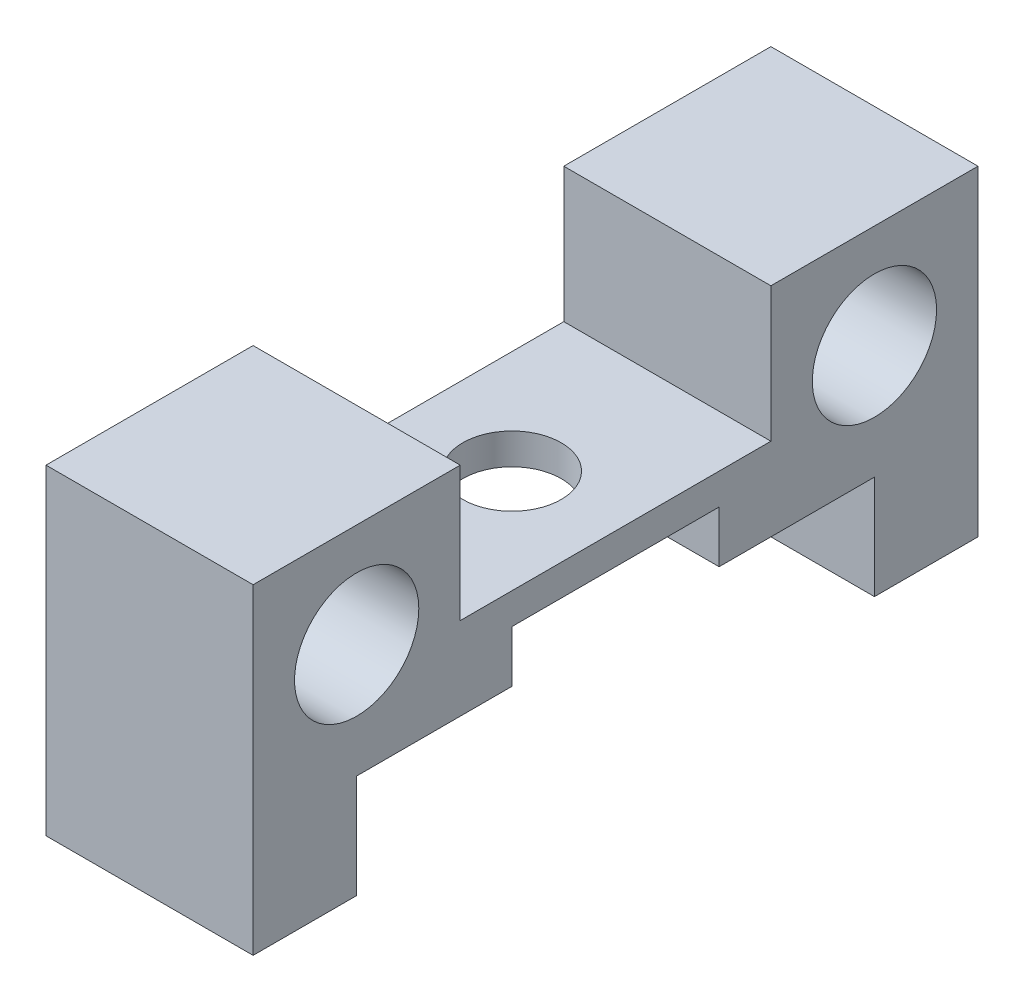
SolidWorks part; units mm, degrees
ref_plane "Plan de face" through (0, 0, 0) normal (0, 0, 1) x (1, 0, 0)
ref_plane "Plan de dessus" through (0, 0, 0) normal (0, 1, 0) x (1, 0, 0)
ref_plane "Plan de droite" through (0, 0, 0) normal (1, 0, 0) x (0, 0, -1)
sketch "Esquisse1" plane through (0, 0, 0) normal (0, 0, 1) x (1, 0, 0)
  line L1 (0, 0) -> (20, 0)
  line L2 (0, 0) -> (0, 31)
  line L3 (0, 31) -> (20, 31)
  line L4 (20, 0) -> (20, 31)
  dimension "D1" = 31
  dimension "D2" = 20
extrude "Extrusion1" add sketch "Esquisse1" along normal blind 70
sketch "Esquisse2" plane through (20, 0, 0) normal (1, 0, 0) x (0, 0, -1)
  line L0 (-70, 31) -> (0, 31) construction
  line L1 (-50, 31) -> (-20, 31)
  line L2 (-50, 31) -> (-50, 18)
  line L4 (-20, 31) -> (-20, 18)
  line L6 (-70, 0) -> (0, 0) construction
  line L7 (-45, 10) -> (-60, 10)
  line L9 (-50, 18) -> (-20, 18)
  line L13 (-45, 15) -> (-25, 15)
  line L14 (-25, 10) -> (-25, 15)
  line L16 (-60, 10) -> (-60, 0)
  line L17 (-60, 0) -> (-10, 0)
  line L18 (-10, 0) -> (-10, 10)
  line L19 (-10, 10) -> (-25, 10)
  line L20 (-45, 10) -> (-45, 15)
  dimension "D1" = 30
  dimension "D3" = 13
  dimension "D4" = 20
  dimension "D5" = 13
  dimension "D7" = 20
  dimension "D8" = 15
  dimension "D9" = 10
  dimension "D11" = 50
  dimension "D12" = 15
  dimension "D13" = 10
extrude "Extrusion2" cut sketch "Esquisse2" against normal through all
sketch "Esquisse3" plane through (0, 18, 0) normal (0, 1, 0) x (1, 0, 0)
  line L0 (20, -50) -> (20, -20) construction
  line L1 (20, 0) -> (0, 0) construction
  circle A0 centre (10, -35) radius 4.75
  dimension "D1" = 9.5
  dimension "D2" = 10
  dimension "D3" = 35
extrude "Extrusion3" cut sketch "Esquisse3" against normal through all
sketch "Esquisse4" plane through (20, 0, 0) normal (1, 0, 0) x (0, 0, -1)
  line L0 (-70, 0) -> (-70, 31) construction
  line L1 (-70, 31) -> (-50, 31) construction
  line L3 (0, 0) -> (0, 31) construction
  line L4 (-20, 31) -> (0, 31) construction
  circle A0 centre (-60, 21) radius 6
  circle A1 centre (-10, 21) radius 6
  dimension "D1" = 12
  dimension "D2" = 12
  dimension "D3" = 10
  dimension "D4" = 10
  dimension "D5" = 10
  dimension "D6" = 10
extrude "Extrusion4" cut sketch "Esquisse4" against normal through all
sketch "Esquisse5" plane through (0, 0, 0) normal (0, -1, 0) x (1, 0, 0)
  line L0 (0, 70) -> (0, 60) construction
  line L1 (20, 70) -> (20, 60) construction
  line L2 (0, 70) -> (20, 70) construction
  line L3 (0, 0) -> (20, 0) construction
  circle A0 centre (5, 65) radius 1.5
  circle A1 centre (5, 5) radius 1.5
  circle A2 centre (15, 65) radius 1.5
  circle A3 centre (15, 5) radius 1.5
  point P8 (0, 65)
  dimension "D1" = 3
  dimension "D2" = 5
  dimension "D3" = 5
  dimension "D4" = 5
  dimension "D5" = 5
extrude "Enlèv. mat.-Extru.1" cut sketch "Esquisse5" against normal blind 10
